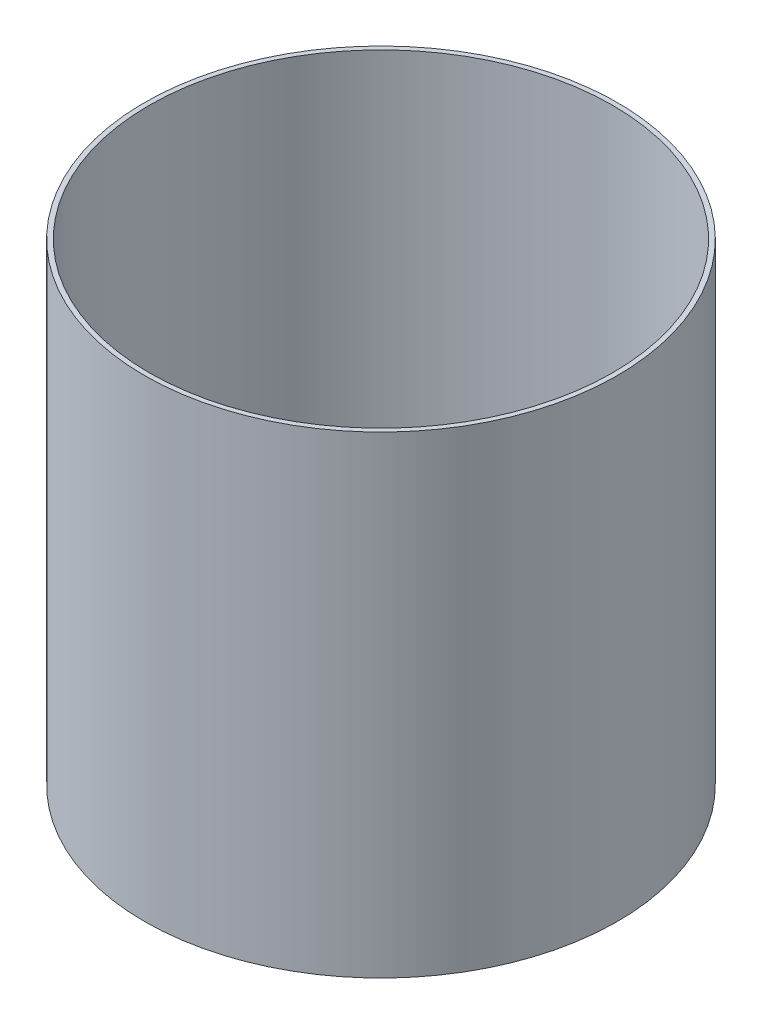
SolidWorks part; units mm, degrees
ref_plane "Front Plane" through (0, 0, 0) normal (0, 0, 1) x (1, 0, 0)
ref_plane "Top Plane" through (0, 0, 0) normal (0, 1, 0) x (1, 0, 0)
ref_plane "Right Plane" through (0, 0, 0) normal (1, 0, 0) x (0, 0, -1)
sketch "Sketch1" plane through (0, 0, 0) normal (0, 1, 0) x (1, 0, 0)
  circle A0 centre (0, 0) radius 50
extrude "Extrude-Thin1" add sketch "Sketch1" along normal blind 100 thin thin type one direction reverse wall 1
